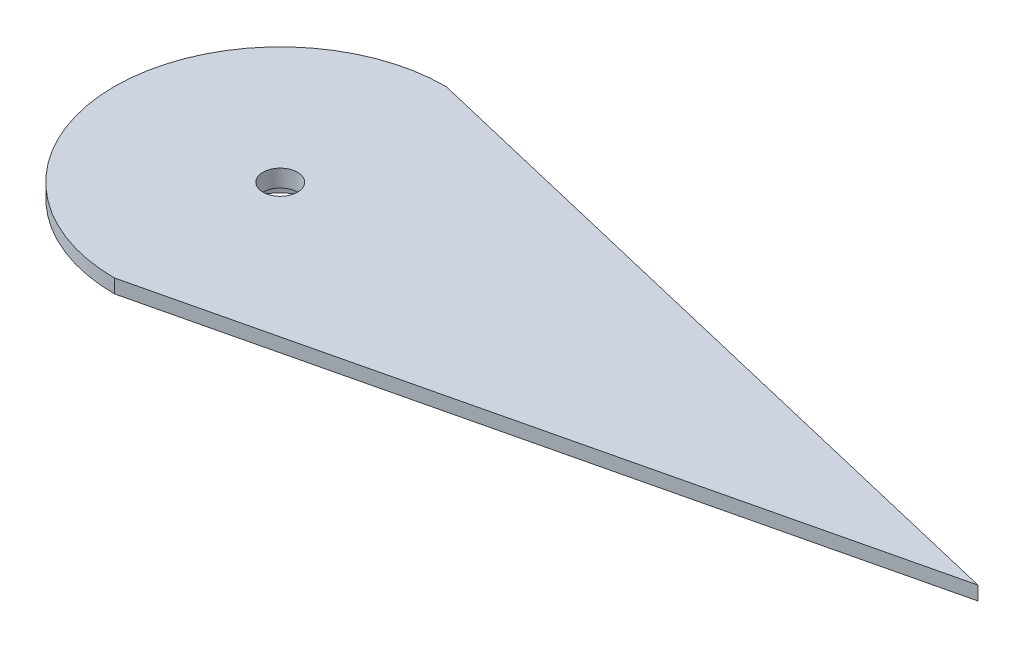
SolidWorks part; units mm, degrees
ref_plane "Front Plane" through (0, 0, 0) normal (0, 0, 1) x (1, 0, 0)
ref_plane "Top Plane" through (0, 0, 0) normal (0, 1, 0) x (1, 0, 0)
ref_plane "Right Plane" through (0, 0, 0) normal (1, 0, 0) x (0, 0, -1)
sketch "Sketch1" plane through (0, 0, 0) normal (0, 1, 0) x (1, 0, 0)
  line L2 (0, 24) -> (101, 0)
  line L3 (0, -24) -> (101, 0)
  arc A0 (0, 24) -> (0, -24) centre (0, 0) ccw
  point P5 (0, -12)
  dimension "D1" = 24
  dimension "D2" = 101
extrude "Boss-Extrude1" add sketch "Sketch1" along normal blind 2
sketch "Sketch2" plane through (0, 0, 0) normal (0, -1, 0) x (1, 0, 0)
  circle A0 centre (0, 0) radius 10
  circle A1 centre (0, 0) radius 8
extrude "Boss-Extrude2" add sketch "Sketch2" along normal blind 5
sketch "Sketch4" plane through (0, 0, 0) normal (0, -1, 0) x (-1, 0, 0)
  circle A0 centre (0, 0) radius 3.25
extrude "Boss-Extrude3" add sketch "Sketch4" along normal blind 0.5
sketch "Sketch5" plane through (0, -0.5, 0) normal (0, -1, 0) x (1, 0, 0)
  circle A0 centre (0, 0) radius 2.5
extrude "Cut-Extrude2" cut sketch "Sketch5" against normal blind 2.5
sketch "Sketch6" plane through (0, -5, 0) normal (0, -1, 0) x (1, 0, 0)
  line L0 (-1, 11.8172) -> (1, 11.8172)
  line L1 (1, 11.8172) -> (0.5862, 8.8172)
  line L2 (0.5862, 8.8172) -> (-0.5862, 8.8172)
  line L3 (-0.5862, 8.8172) -> (-1, 11.8172)
  circle A1 centre (0, 0) radius 8 construction
  point P4 (0, 8.8172)
  point P5 (0, 11.8172)
  point P7 (0.6095, 9.0738)
  point P8 (0.5862, 8.8172)
  point P9 (0, 8)
  dimension "D1" = 3
  dimension "D2" = 2
extrude "Cut-Extrude3" cut sketch "Sketch6" against normal blind 5
fillet "Fillet1" radius 0.5 2 edges at (0.7455, -2.5, 9.9722) (-0.7455, -2.5, 9.9722)
pattern_circular "CirPattern5" count 24 every 15 about axis through (0, 0, 0) along (0, 1, 0) of "Fillet1", "Cut-Extrude3"
